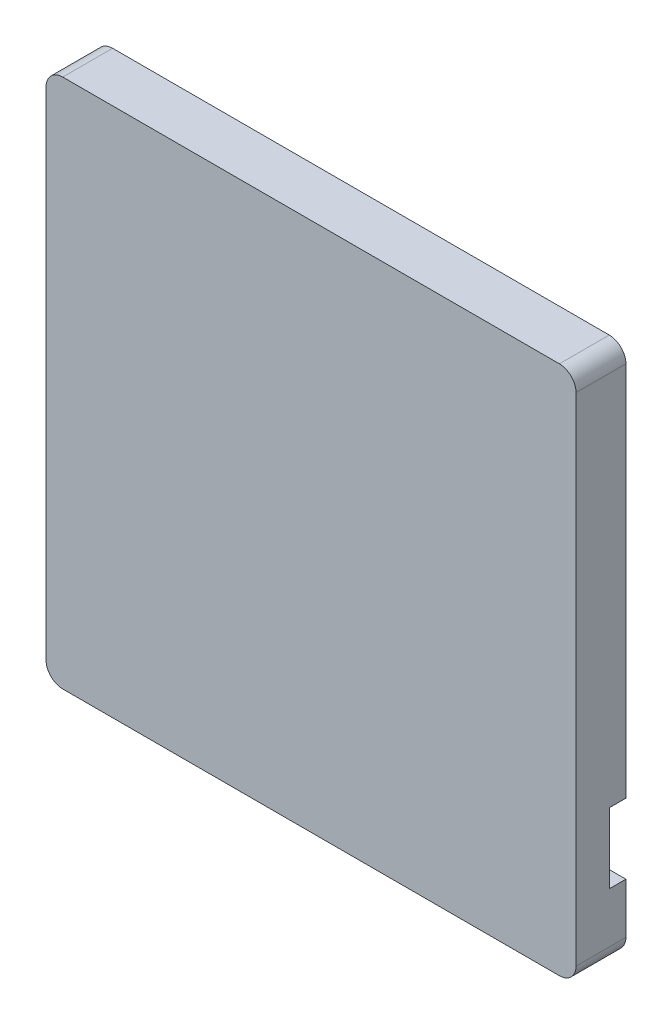
SolidWorks part; units mm, degrees
ref_plane "前视基准面" through (0, 0, 0) normal (0, 0, 1) x (1, 0, 0)
ref_plane "上视基准面" through (0, 0, 0) normal (0, 1, 0) x (1, 0, 0)
ref_plane "右视基准面" through (0, 0, 0) normal (1, 0, 0) x (0, 0, -1)
other "Configuration Table"
sketch "草图2" plane through (0, 0, 0) normal (0, 0, 1) x (1, 0, 0)
  line L68 (-147.5217, 156.6143) -> (171.2964, 156.6143)
  line L85 (-147.5217, 156.6143) -> (-147.5217, -162.2039)
  line L88 (-147.5217, -162.2039) -> (171.2964, -162.2039)
  line L90 (171.2964, 156.6143) -> (171.2964, -162.2039)
  line L92 (108.8874, -31.2948) -> (133.3874, -31.2948)
  line L93 (133.3874, -31.2948) -> (133.3874, -37.2948)
  line L94 (133.3874, -37.2948) -> (133.3874, -73.7948)
  line L95 (133.3874, -73.7948) -> (124.8874, -73.7948)
  line L97 (124.8874, -129.2948) -> (108.8874, -129.2948)
  line L98 (108.8874, -129.2948) -> (108.8874, -74.7948)
  line L99 (-54.1126, -80.7948) -> (-54.1126, -121.7948)
  line L100 (-54.1126, -121.7948) -> (77.8874, -121.7948)
  line L101 (77.8874, -121.7948) -> (77.8874, -80.7948)
  line L103 (129.8874, -129.3529) -> (129.8874, -121.8948)
  line L104 (129.8874, -121.8948) -> (204.8874, -121.8948)
  line L105 (204.8874, -121.8948) -> (204.8874, -79.6948)
  line L106 (204.8874, -79.6948) -> (129.8874, -79.6948)
  line L107 (129.8874, -79.6948) -> (129.8874, -72.6948)
  line L110 (124.151, -129.2948) -> (129.8874, -129.3529)
  line L111 (114.8874, -74.7948) -> (114.8874, 87.2052)
  line L112 (101.8874, 100.2052) -> (-78.1126, 100.2052)
  line L113 (-91.1126, 87.2052) -> (-91.1126, -74.7948)
  line L114 (-78.1126, -87.7948) -> (-48.1126, -87.7948)
  line L118 (71.8874, -87.7948) -> (101.8874, -87.7948)
  arc A23 (114.8874, 87.2052) -> (101.8874, 100.2052) centre (101.8874, 87.2052) ccw
  arc A24 (-78.1126, 100.2052) -> (-91.1126, 87.2052) centre (-78.1126, 87.2052) ccw
  arc A25 (-91.1126, -74.7948) -> (-78.1126, -87.7948) centre (-78.1126, -74.7948) ccw
  arc A26 (101.8874, -87.7948) -> (114.8874, -74.7948) centre (101.8874, -74.7948) ccw
  circle A28 centre (11.8874, -2.7948) radius 42
  circle A29 centre (11.8874, -2.7948) radius 159.4091 construction
extrude "凸台-拉伸1" add sketch "草图2" along normal blind 10 contours A26 L118 L101 L100 L99 L114 A25 L113 A24 L112 A23 L111 L92 L93 L94 L95 L107 L106 L90 L68 L85 L88 L104 L103 L110 L97 L98
sketch "草图4" plane through (0, 0, 10) normal (0, 0, 1) x (1, 0, 0)
  line L1 (171.2964, -162.2039) -> (-147.5217, -162.2039)
  line L2 (171.2964, -162.2039) -> (171.2964, 156.6143)
  line L3 (171.2964, 156.6143) -> (-147.5217, 156.6143)
  line L4 (-147.5217, -162.2039) -> (-147.5217, 156.6143)
extrude "凸台-拉伸3" add sketch "草图4" along normal blind 20
sketch "草图6" plane through (0, 0, 10) normal (0, 0, -1) x (-1, 0, 0)
  arc A1 (-56.8874, -2.7948) -> (33.1126, -2.7948) centre (-11.8874, -2.7948) ccw construction
  circle A2 centre (-11.8874, -2.7948) radius 45
  circle A3 centre (-11.8874, -2.7948) radius 45
  circle A4 centre (-11.8874, -2.7948) radius 42
  dimension "D1" = 3
extrude "凸台-拉伸4" add sketch "草图6" along normal blind 85 contours A4
fillet "圆角1" radius 10 4 edges at (-147.5217, -162.2039, 15) (-147.5217, 156.6143, 15) (171.2964, 156.6143, 15) (171.2964, -162.2039, 15)
